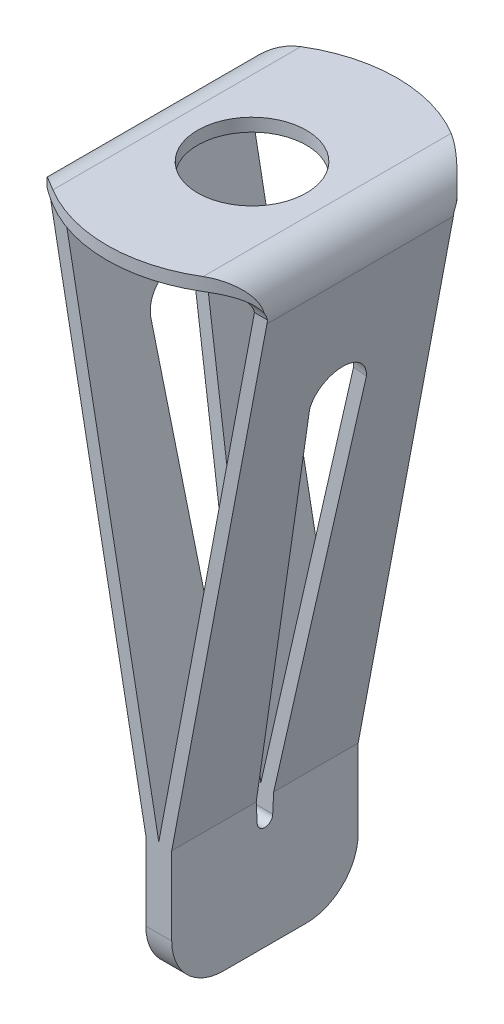
SolidWorks part; units mm, degrees
ref_plane "Plano frontal" through (0, 0, 0) normal (0, 0, 1) x (1, 0, 0)
ref_plane "Plano superior" through (0, 0, 0) normal (0, 1, 0) x (1, 0, 0)
ref_plane "Plano direito" through (0, 0, 0) normal (1, 0, 0) x (0, 0, -1)
sketch "Esboço1" plane through (0, 0, 0) normal (0, 1, 0) x (1, 0, 0)
  line L0 (0, 0) -> (12.8498, 0) construction
  line L1 (2.0791, 1.8) -> (14, 1.8)
  line L2 (15, 0.8) -> (15, -0.8)
  line L3 (14, -1.8) -> (2.0791, -1.8)
  line L4 (0, 0) -> (0, -2.75) construction
  line L5 (0, 0) -> (0, 2.75) construction
  line L6 (4.9785, 0.5499) -> (12.8574, 0.15)
  line L7 (13, 0.15) -> (13, -0.15) construction
  line L8 (12.8574, -0.15) -> (4.9785, -0.5499)
  line L9 (4.4, -0.55) -> (4.4, 0.55) construction
  line L10 (-12.8574, -0.15) -> (-4.9785, -0.5499)
  line L11 (-4.9785, 0.5499) -> (-12.8574, 0.15)
  line L12 (-2.0791, 1.8) -> (-14, 1.8)
  line L13 (-15, 0.8) -> (-15, -0.8)
  line L14 (-14, -1.8) -> (-2.0791, -1.8)
  arc A0 (2.0791, 1.8) -> (-2.0791, 1.8) centre (0, 0) ccw
  arc A1 (-2.0791, -1.8) -> (2.0791, -1.8) centre (0, 0) ccw
  arc A2 (15, -0.8) -> (14, -1.8) centre (14, -0.8) cw
  arc A3 (14, 1.8) -> (15, 0.8) centre (14, 0.8) cw
  arc A4 (12.8574, 0.15) -> (12.8574, -0.15) centre (12.8498, 0) cw
  arc A5 (4.9785, 0.5499) -> (4.9785, -0.5499) centre (4.9506, 0) ccw
  arc A6 (-12.8574, 0.15) -> (-12.8574, -0.15) centre (-12.8498, 0) ccw
  arc A7 (-4.9785, 0.5499) -> (-4.9785, -0.5499) centre (-4.9506, 0) cw
  arc A8 (-14, 1.8) -> (-15, 0.8) centre (-14, 0.8) ccw
  arc A9 (-15, -0.8) -> (-14, -1.8) centre (-14, -0.8) ccw
  circle A10 centre (0, 0) radius 1.05
  dimension "D1" = 5.5
  dimension "D4" = 1
  dimension "D10" = 1.0998
  dimension "D11" = 2.1
  dimension "D2" = 3.6
  dimension "D3" = 15
  dimension "D5" = 1.1
  dimension "D6" = 0.3
  dimension "D7" = 2
  dimension "D8" = 8.6
  dimension "D9" = 0.3
extrude "Ressalto-extrusão1" add sketch "Esboço1" along normal blind 0.25
sketch "Esboço4" plane through (0, 0, 0) normal (0, 0, 1) x (1, 0, 0)
  line L0 (-2.3004, 0.5995) -> (0.2158, -12.7149) construction
  line L1 (0, 0) -> (0, -16.568) construction
  line L2 (2.0791, 0.25) -> (-2.0791, 0.25) construction
  line L3 (-1.45, 0.25) -> (-1.45, 0.5566) construction
  line L4 (-2.1, 0.25) -> (-2.1, -0.4) construction
  line L5 (0, -10.2266) -> (0, -12.76)
  line L6 (-1.45, -0.4) -> (-1.45, 0.25) construction
  line L7 (-15, 0.25) -> (-1.45, 0.25) construction
  line L8 (0, 0.6012) -> (0, 0) construction
  line L9 (-0.25, -10.25) -> (-0.25, -12.76)
  line L10 (-1.843, -0.4743) -> (0, -10.2266)
  line L11 (-2.0887, -0.5207) -> (-0.25, -10.25)
  line L12 (-0.25, -12.76) -> (0, -12.76)
  line L13 (-4.887, -12.75) -> (0, -12.75) construction
  line L14 (-1.45, -0.4) -> (-2.1, -0.4) construction
  line L15 (-1.45, -0.4) -> (-2.0887, -0.5207) construction
  line L16 (-0.25, -12.75) -> (-0.25, -10.25) construction
  line L17 (-1.45, 0.25) -> (-1.45, 0)
  circle A0 centre (-1.45, -0.4) radius 0.65 construction
  circle A1 centre (-1.45, -0.4) radius 0.4 construction
  arc A2 (-2.0887, -0.5207) -> (-1.45, 0.25) centre (-1.45, -0.4) cw
  arc A3 (-1.843, -0.4743) -> (-1.45, 0) centre (-1.45, -0.4) cw
  dimension "D1" = 1.3
  dimension "D6" = 2.5
  dimension "D8" = 1.45
  dimension "D3" = 0.25
  dimension "D4" = 13
  dimension "D5" = 0.25
  dimension "D7" = 1.14
  dimension "D9" = 0.25
  dimension "D10" = 2.51
  dimension "D2" = 2.1
extrude "Ressalto-extrusão2" add sketch "Esboço4" along normal mid plane 3.6 separate body
fillet "Filete1" radius 1 2 edges at (-0.125, -12.76, -1.8) (-0.125, -12.76, 1.8)
sketch "Esboço16" plane through (-0.25, 0, 0) normal (-1, 0, 0) x (0, 0, 1)
  line L0 (-1.8, -10.61) -> (1.8, -10.61) construction
  line L1 (-1.8, -10.25) -> (-1.8, -11.76) construction
  line L2 (1.8, -10.25) -> (1.8, -11.76) construction
  line L3 (0.8, -12.76) -> (-0.8, -12.76) construction
  line L4 (-1.8, -10.76) -> (1.8, -10.76) construction
  line L5 (0.15, -10.61) -> (0.5499, -2.7385)
  line L6 (-0.5499, -2.7385) -> (-0.15, -10.61)
  line L7 (0, 0) -> (0, -12.76) construction
  line L8 (-1.8, -2.16) -> (1.8, -2.16) construction
  line L9 (1.8, -0.5207) -> (1.8, -10.25) construction
  line L10 (-1.8, -0.5207) -> (-1.8, -10.25) construction
  arc A0 (-0.15, -10.61) -> (0.15, -10.61) centre (0, -10.61) ccw
  arc A1 (-0.5499, -2.7385) -> (0.5499, -2.7385) centre (0, -2.7106) cw
  point P6 (0, -12.76)
  dimension "D3" = 0.15
  dimension "D5" = 0.5506
  dimension "D1" = 2.15
  dimension "D2" = 2
  dimension "D4" = 8.6
extrude "Ressalto-extrusão4" add sketch "Esboço16" along normal mid plane 4 separate body
sketch "Esboço17" plane through (-2.1117, -0.3991, 0) normal (-0.9826, -0.1857, 0) x (0, 0, 1)
  line L0 (0, 0) -> (0, -12.4916) construction
  line L1 (0.8, -12.4916) -> (-0.8, -12.4916) construction
  line L2 (1.8, -10.0253) -> (-1.8, -10.0253) construction
  line L3 (-0.55, -2.5134) -> (-0.175, -10.0253)
  line L4 (0.175, -10.0253) -> (1.2015, -10.0253)
  line L5 (-0.9157, -1.9353) -> (2.3694, -1.9353) construction
  line L7 (0.55, -2.5134) -> (0.175, -10.0253)
  line L8 (-0.175, -10.0253) -> (0.175, -10.0253) construction
  line L10 (-1.2911, -10.0253) -> (-1.2911, -1.562)
  line L11 (-1.2911, -1.562) -> (1.2015, -1.562)
  line L12 (1.2015, -1.562) -> (1.2015, -10.0253)
  line L14 (-0.175, -10.0253) -> (-1.2911, -10.0253)
  arc A0 (-0.55, -2.5134) -> (0.55, -2.5134) centre (0, -2.486) cw
  dimension "D1" = 1.1
  dimension "D3" = 0.35
  dimension "D2" = 8.09
extrude "Corte-extrusão6" cut sketch "Esboço17" against normal mid plane 10
combine bodies "Combinar2" operation type subtract main body 110 bodies to subtract 120
mirror "Espelhar1" about plane through (0, 0, 0) normal (1, 0, 0) of bodies 121 110
sketch "Esboço5" plane through (0, 0.25, 0) normal (0, 1, 0) x (1, 0, 0)
  line L5 (-2.1, 1.852) -> (-2.1, -1.852)
  line L6 (2.1, 1.852) -> (2.1, -1.852)
  line L7 (-2.1, 1.8) -> (-2.1, -1.8) construction
  line L8 (2.1, -1.8) -> (2.1, 1.8) construction
  circle A2 centre (0, 0) radius 1.05 construction
  arc A3 (-2.1, -1.852) -> (2.1, -1.852) centre (0, 0) ccw
  arc A4 (2.1, 1.852) -> (-2.1, 1.852) centre (0, 0) ccw
  circle A5 centre (0, 0) radius 1.05
  dimension "D1" = 5.6
extrude "Ressalto-extrusão3" add sketch "Esboço5" against normal blind 0.7 separate body
sketch "Esboço6" plane through (0, 0, 0) normal (0, 0, 1) x (1, 0, 0)
  line L0 (-1.45, 0.25) -> (-1.45, 0.5972)
  line L1 (-1.45, 0.5972) -> (-2.4286, 0.5972)
  line L2 (-2.4286, 0.5972) -> (-2.4286, -0.5207)
  line L3 (-2.4286, -0.5207) -> (-2.0887, -0.5207)
  line L4 (1.45, 0.25) -> (1.45, 0.7297)
  line L5 (1.45, 0.7297) -> (2.6887, 0.7297)
  line L6 (2.6887, 0.7297) -> (2.6887, -0.5207)
  line L7 (2.6887, -0.5207) -> (2.0887, -0.5207)
  line L8 (-1.45, 0) -> (1.45, 0)
  line L13 (-1.843, -0.4743) -> (1.843, -0.4743)
  arc A0 (-1.45, 0.25) -> (-2.0887, -0.5207) centre (-1.45, -0.4) ccw construction
  arc A1 (-1.45, 0.25) -> (-2.0887, -0.5207) centre (-1.45, -0.4) ccw
  arc A2 (2.0887, -0.5207) -> (1.45, 0.25) centre (1.45, -0.4) ccw construction
  arc A3 (2.0887, -0.5207) -> (1.45, 0.25) centre (1.45, -0.4) ccw
  arc A5 (-1.45, 0) -> (-1.843, -0.4743) centre (-1.45, -0.4) ccw construction
  arc A7 (-1.45, 0) -> (-1.843, -0.4743) centre (-1.45, -0.4) ccw
  arc A8 (1.843, -0.4743) -> (1.45, 0) centre (1.45, -0.4) ccw construction
  arc A9 (1.843, -0.4743) -> (1.45, 0) centre (1.45, -0.4) ccw
extrude "Corte-extrusão1" cut sketch "Esboço6" against normal mid plane 10
combine bodies "Combinar1" operation type add bodies to combine 113 111 121
sketch "Esboço7" plane through (0, 0, 0) normal (1, 0, 0) x (0, 0, -1)
  line L1 (2.3953, 0) -> (2.8, 0) construction
  line L3 (2.3953, 0) -> (3.16, 0)
  line L4 (3.16, 0) -> (3.16, -0.6188)
  line L5 (3.16, -0.6188) -> (1.8, -0.6188)
  line L6 (1.8, -0.5207) -> (1.8, -10.25) construction
  line L7 (1.8, -0.6188) -> (1.8, -0.45)
  line L8 (-2.1045, -0.45) -> (-1.8542, -0.45) construction
  line L9 (-1.8, -0.45) -> (-1.8, -0.5207) construction
  line L12 (-1.8, -0.45) -> (-1.8, -0.595)
  line L13 (-1.8, -0.5207) -> (-1.8, -10.25) construction
  line L14 (-1.8, -0.595) -> (-2.9894, -0.595)
  line L15 (-2.9894, -0.595) -> (-2.9894, 0)
  line L16 (-2.9894, 0) -> (-2.3953, 0)
  line L17 (1.8, -0.5207) -> (1.8, -0.45) construction
  arc A0 (2.3953, 0) -> (1.8, -0.45) centre (2.3953, -0.6188) ccw
  arc A1 (-1.8, -0.45) -> (-2.3953, 0) centre (-2.3953, -0.6188) ccw
  spline S1 degree 3 poles (2.3953, 0) (2.3301, 0) (2.2571, -0.0422) (2.1663, -0.1601) (2.1393, -0.2092) (2.1045, -0.3227) (2.0977, -0.3885) (2.1045, -0.45) knots 0 0 0 0 0.5 0.5 0.75 0.75 1 1 1 1 construction
extrude "Corte-extrusão2" cut sketch "Esboço7" against normal mid plane 30
delete or keep bodies "Corpo-Excluir/Manter 1" type delete bodies bodies 101
